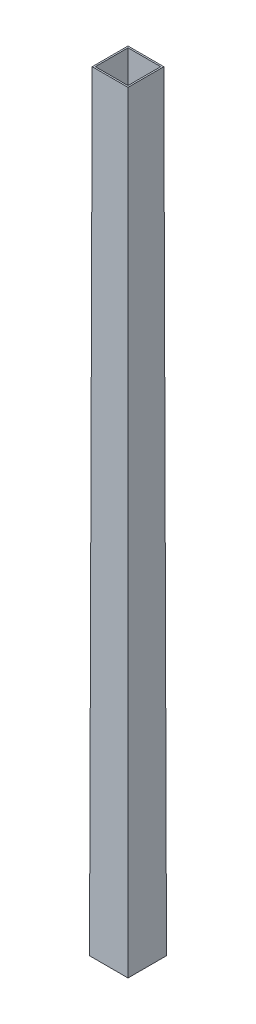
SolidWorks part; units mm, degrees
ref_plane "前视基准面" through (0, 0, 0) normal (0, 0, 1) x (1, 0, 0)
ref_plane "上视基准面" through (0, 0, 0) normal (0, 1, 0) x (1, 0, 0)
ref_plane "右视基准面" through (0, 0, 0) normal (1, 0, 0) x (0, 0, -1)
other "Configuration Table"
sketch "草图1" plane through (0, 0, 0) normal (0, 1, 0) x (1, 0, 0)
  line L1 (-2.5, 2.5) -> (2.5, 2.5)
  line L2 (-2.5, 2.5) -> (-2.5, -2.5)
  line L3 (-2.5, -2.5) -> (2.5, -2.5)
  line L4 (2.5, 2.5) -> (2.5, -2.5)
  line L5 (-2.5, 2.5) -> (2.5, -2.5) construction
  line L6 (-2.5, -2.5) -> (2.5, 2.5) construction
  point P0 (0, 0)
  dimension "D1" = 5
  dimension "D2" = 5
ref_plane "基准面3" through (0, 100, 0) normal (0, 1, 0) x (1, 0, 0)
sketch "草图2" plane through (0, 100, 0) normal (0, 1, 0) x (1, 0, 0)
  line L0 (-2.5, 2.5) -> (2.5, -2.5) construction
  line L1 (-2.3255, 2.3255) -> (2.3255, 2.3255)
  line L2 (-2.3255, 2.3255) -> (-2.3255, -2.3255)
  line L3 (-2.3255, -2.3255) -> (2.3255, -2.3255)
  line L4 (2.3255, 2.3255) -> (2.3255, -2.3255)
  line L5 (-2.3255, 2.3255) -> (2.3255, -2.3255) construction
  line L6 (-2.3255, -2.3255) -> (2.3255, 2.3255) construction
  point P0 (0, 0)
  dimension "D1" = 4.6509
  dimension "D2" = 4.6509
loft "放样1" add profiles "草图2", "草图1"
shell "抽壳1" thickness 0.2
equation "\"Length\"= 100mm"
equation "\"Width_Large\" = 5mm"
equation "\"Thickness\" = 0.2mm"
equation "\"Taper\" = 0.1mm"
equation "\"D1@草图1\"=\"Width_Large\""
equation "\"D2@草图1\"=\"Width_Large\""
equation "\"Width_Small\"= \"Width_Large\" - 2 * \"Length\" * tan ( \"Taper\" )"
equation "\"D1@基准面3\"= \"Length\""
equation "\"D1@草图2\"=\"Width_Small\""
equation "\"D1@抽壳1\"=\"Thickness\""
